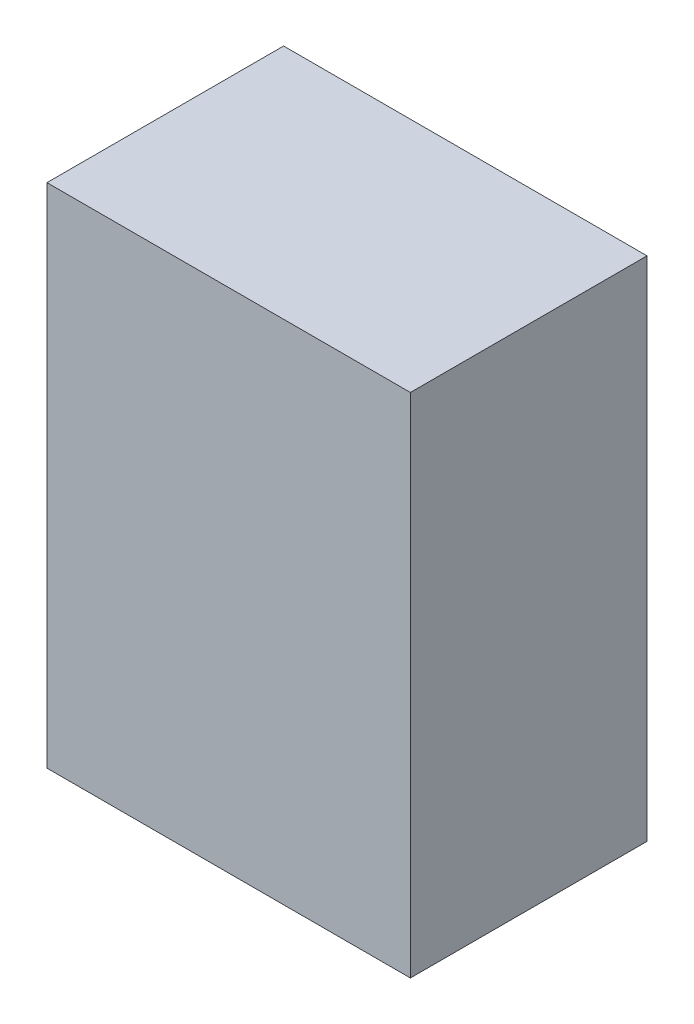
SolidWorks part; units mm, degrees
ref_plane "Front Plane" through (0, 0, 0) normal (0, 0, 1) x (1, 0, 0)
ref_plane "Top Plane" through (0, 0, 0) normal (0, 1, 0) x (1, 0, 0)
ref_plane "Right Plane" through (0, 0, 0) normal (1, 0, 0) x (0, 0, -1)
sketch "Sketch1" plane through (0, 0, 0) normal (0, 1, 0) x (1, 0, 0)
  line L1 (0, 0) -> (546.1, 0)
  line L2 (0, 0) -> (0, 355.6)
  line L3 (0, 355.6) -> (546.1, 355.6)
  line L4 (546.1, 0) -> (546.1, 355.6)
  dimension "D1" = 546.1
  dimension "D2" = 355.6
extrude "Extrude1" add sketch "Sketch1" along normal blind 762
